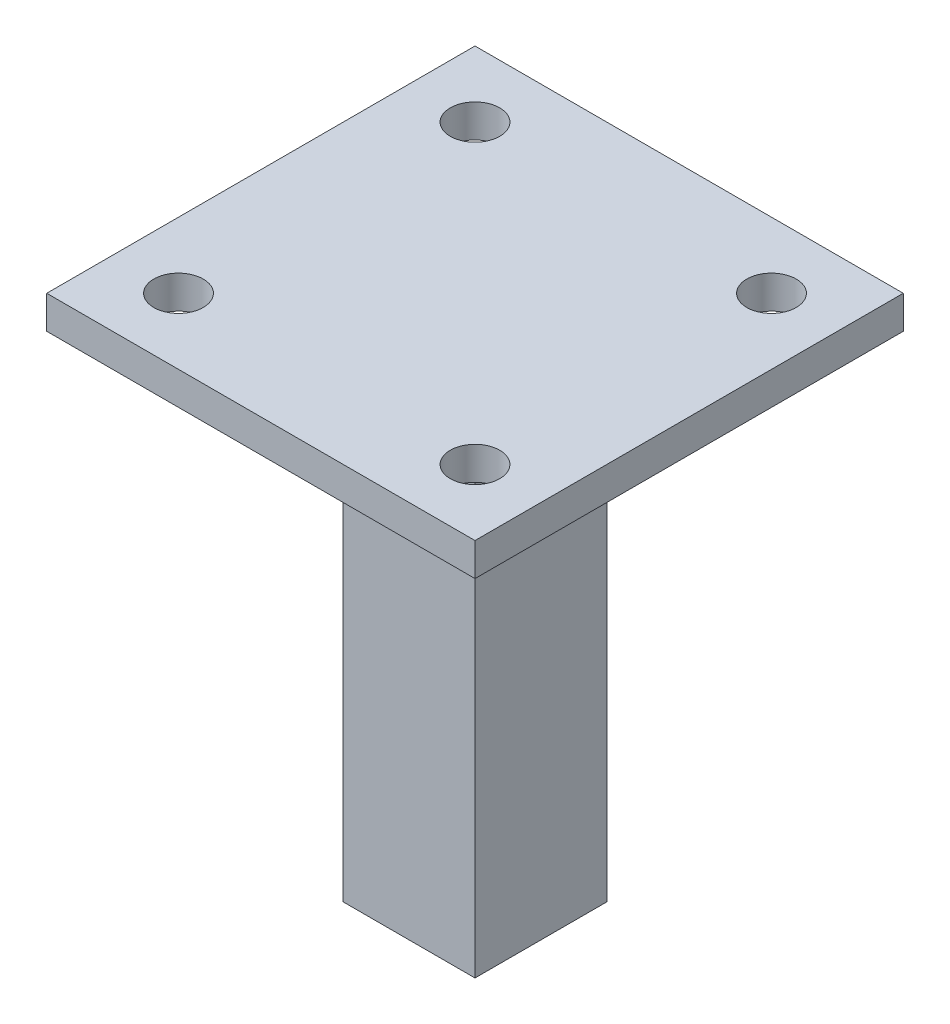
SolidWorks part; units mm, degrees
ref_plane "Front Plane" through (0, 0, 0) normal (0, 0, 1) x (1, 0, 0)
ref_plane "Top Plane" through (0, 0, 0) normal (0, 1, 0) x (1, 0, 0)
ref_plane "Right Plane" through (0, 0, 0) normal (1, 0, 0) x (0, 0, -1)
sketch "Sketch1" plane through (0, 0, 0) normal (0, 1, 0) x (1, 0, 0)
  line L1 (-20, -20) -> (20, -20)
  line L2 (-20, -20) -> (-20, 20)
  line L3 (-20, 20) -> (20, 20)
  line L4 (20, -20) -> (20, 20)
  line L5 (-20, -20) -> (20, 20) construction
  line L6 (-20, 20) -> (20, -20) construction
  point P0 (0, 0)
  dimension "D1" = 40
  dimension "D2" = 40
extrude "Boss-Extrude1" add sketch "Sketch1" along normal blind 150
sketch "Sketch2" plane through (0, 150, 0) normal (0, 1, 0) x (1, 0, 0)
  line L1 (-65, -65) -> (65, -65)
  line L2 (-65, -65) -> (-65, 65)
  line L3 (-65, 65) -> (65, 65)
  line L4 (65, -65) -> (65, 65)
  line L5 (-65, -65) -> (65, 65) construction
  line L6 (-65, 65) -> (65, -65) construction
  circle A0 centre (-45, -45) radius 7.5
  circle A1 centre (45, -45) radius 7.5
  circle A2 centre (45, 45) radius 7.5
  circle A3 centre (-45, 45) radius 7.5
  point P0 (0, 0)
  point P14 (0, 0)
  point P15 (0, 0)
  point P16 (0, 0)
  point P17 (0, 0)
  dimension "D4" = 15
  dimension "D1" = 130
  dimension "D2" = 130
  dimension "D3" = 20
extrude "Boss-Extrude2" add sketch "Sketch2" along normal blind 10
